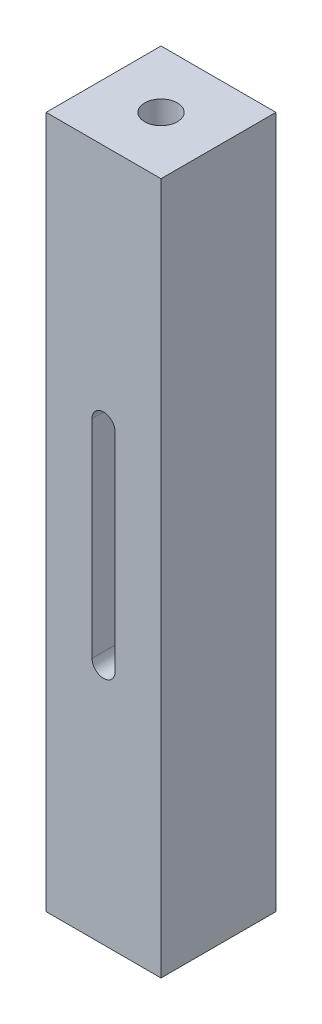
SolidWorks part; units mm, degrees
ref_plane "Front Plane" through (0, 0, 0) normal (0, 0, 1) x (1, 0, 0)
ref_plane "Top Plane" through (0, 0, 0) normal (0, 1, 0) x (1, 0, 0)
ref_plane "Right Plane" through (0, 0, 0) normal (1, 0, 0) x (0, 0, -1)
sketch "Sketch2" plane through (0, 0, 0) normal (0, 1, 0) x (1, 0, 0)
  line L1 (0, 0) -> (-24.9, 0)
  line L2 (0, 0) -> (0, 24.9)
  line L3 (0, 24.9) -> (-24.9, 24.9)
  line L4 (-24.9, 0) -> (-24.9, 24.9)
  circle A0 centre (-12.45, 12.45) radius 3.55
  point P8 (0, 12.45)
  point P10 (-12.45, 0)
  dimension "D2" = 7.1
  dimension "D1" = 24.9
extrude "Boss-Extrude1" add sketch "Sketch2" along normal blind 150
sketch "Sketch3" plane through (0, 0, 0) normal (0, 0, 1) x (1, 0, 0)
  line L0 (-14.95, 97.5) -> (-14.95, 52.5)
  line L1 (-9.95, 97.5) -> (-9.95, 52.5)
  line L3 (-24.9, 0) -> (0, 0) construction
  line L4 (-24.9, 150) -> (-24.9, 0) construction
  arc A0 (-14.95, 97.5) -> (-9.95, 97.5) centre (-12.45, 97.5) cw
  arc A1 (-14.95, 52.5) -> (-9.95, 52.5) centre (-12.45, 52.5) ccw
  point P9 (-12.45, 0)
  point P14 (-24.9, 75)
  point P15 (-14.95, 75)
  point P16 (-12.45, 100)
  point P17 (-12.45, 50)
  dimension "D1" = 5
  dimension "D2" = 50
extrude "Cut-Extrude1" cut sketch "Sketch3" against normal up to next contours L0 A1 L1 A0
